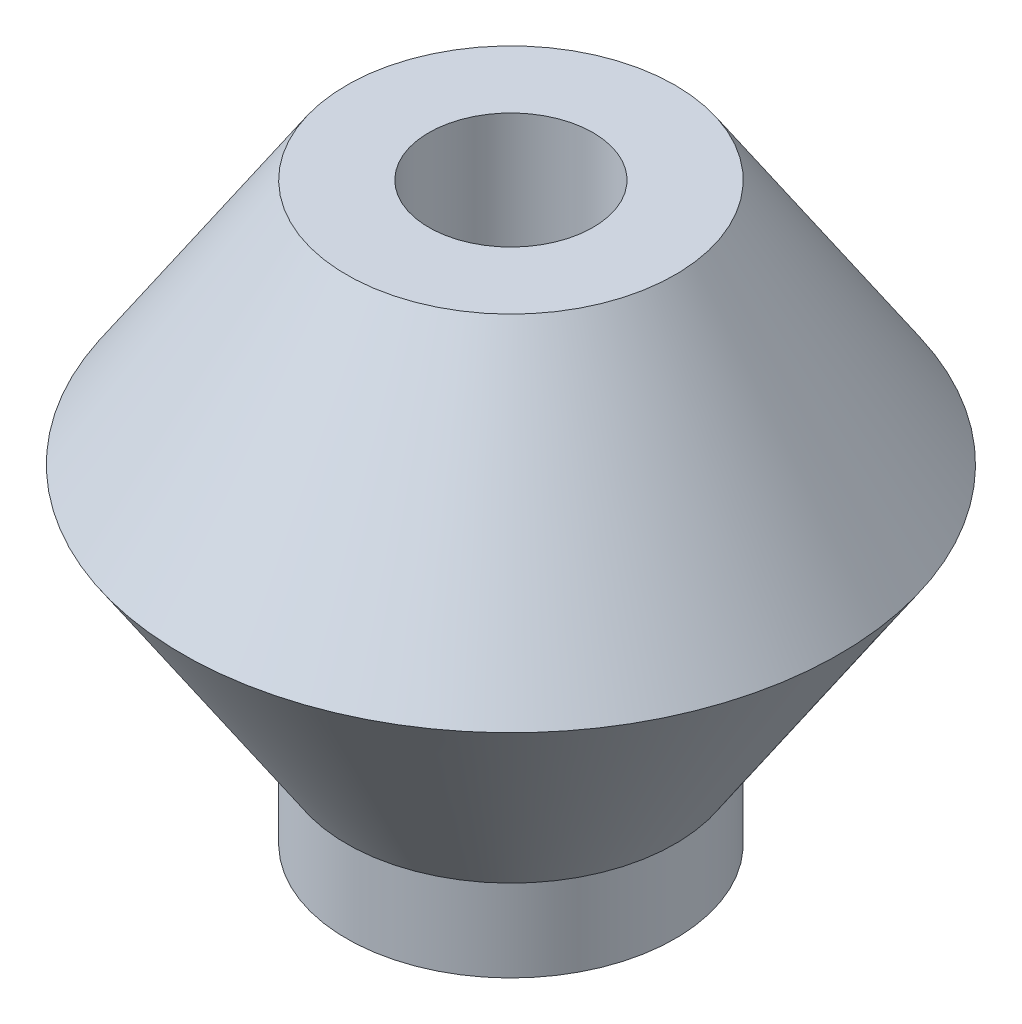
SolidWorks part; units mm, degrees
ref_plane "Front Plane" through (0, 0, 0) normal (0, 0, 1) x (1, 0, 0)
ref_plane "Top Plane" through (0, 0, 0) normal (0, 1, 0) x (1, 0, 0)
ref_plane "Right Plane" through (0, 0, 0) normal (1, 0, 0) x (0, 0, -1)
sketch "Sketch1" plane through (0, 0, 0) normal (0, 0, 1) x (1, 0, 0)
  line L0 (2, 0) -> (2, 14)
  line L1 (2, 14) -> (4, 14)
  line L2 (4, 14) -> (8, 8)
  line L3 (8, 8) -> (4, 2)
  line L4 (4, 2) -> (4, 0)
  line L5 (4, 0) -> (2, 0)
  line L6 (0, 0) -> (0, 10.7307) construction
  point P9 (0, 0)
  dimension "D1" = 4
  dimension "D2" = 2
  dimension "D3" = 14
  dimension "D4" = 8
  dimension "D5" = 2
  dimension "D6" = 6
revolve "Revolve1" add sketch "Sketch1" angle 360 about L6
